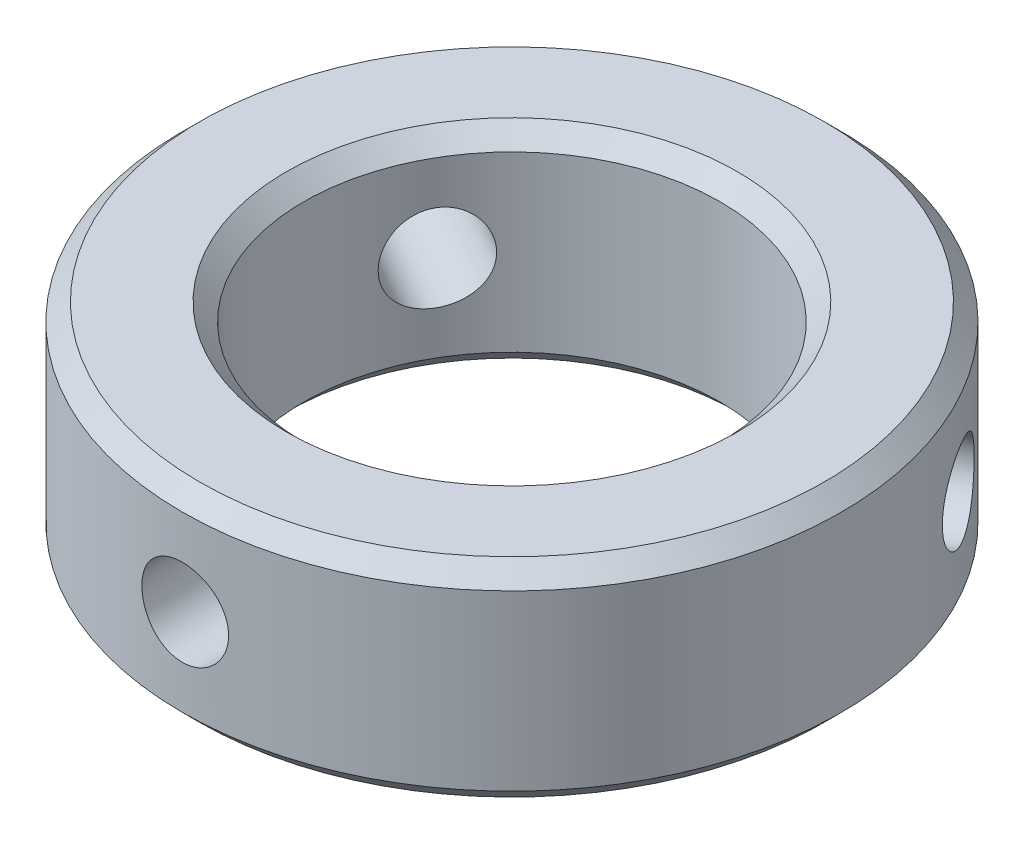
SolidWorks part; units mm, degrees
material "Aleación 1060"
ref_plane "Alzado" through (0, 0, 0) normal (0, 0, 1) x (1, 0, 0)
ref_plane "Planta" through (0, 0, 0) normal (0, 1, 0) x (1, 0, 0)
ref_plane "Vista lateral" through (0, 0, 0) normal (1, 0, 0) x (0, 0, -1)
sketch "Croquis1" plane through (0, 0, 0) normal (0, 1, 0) x (1, 0, 0)
  circle A0 centre (0, 0) radius 9.5
  circle A1 centre (0, 0) radius 6
  dimension "D1" = 19
  dimension "D2" = 12
extrude "Saliente-Extruir1" add sketch "Croquis1" along normal blind 6
ref_plane "Plano1" through (0, 0, 9.5) normal (0, 0, 1) x (1, 0, 0)
sketch "Croquis2" plane through (0, 0, 9.5) normal (0, 0, 1) x (1, 0, 0)
  line L0 (-9.5, 0) -> (9.5, 0) construction
  point P0 (0, 3)
  dimension "D1" = 3
hole_wizard "Taladro roscado M31" positions "Croquis2" profile "Croquis3" tap size "M3" standard "ISO"
sketch "Croquis3" plane through (0, 3, 9.5) normal (1, 0, 0) x (0, -1, 0)
  line L0 (0, 0) -> (0, 9.2511)
  line L1 (0, 9.2511) -> (1.25, 8.5)
  line L2 (1.25, 8.5) -> (1.25, 0)
  line L5 (1.25, 0) -> (0, 0)
  line L10 (0, 9.2511) -> (-1.25, 8.5) construction
  line L11 (0, -6.35) -> (0, 107.95) construction
  dimension "Diámetro de perforador para roscar" = 2.5
  dimension "Profundidad de perforador para roscar" = 8.5
  dimension "Ángulo de perforador" = 118
cosmetic thread "Rosca de taladro1" parameters "D1"=6, "D2"=3
pattern_circular "MatrizC1" count 3 every 120 about axis through (0, 0, 0) along (0, 1, 0) of "Taladro roscado M31"
cosmetic thread "Rosca de taladro2" parameters "D1"=6, "D2"=3
cosmetic thread "Rosca de taladro3" parameters "D1"=6, "D2"=3
chamfer "Chaflán1" distance 0.5 angle 45 2 edges at (0, 6, 6) (0, 0, 6)
chamfer "Chaflán2" distance 0.5 angle 45 2 edges at (0, 6, 9.5) (0, 0, 9.5)
